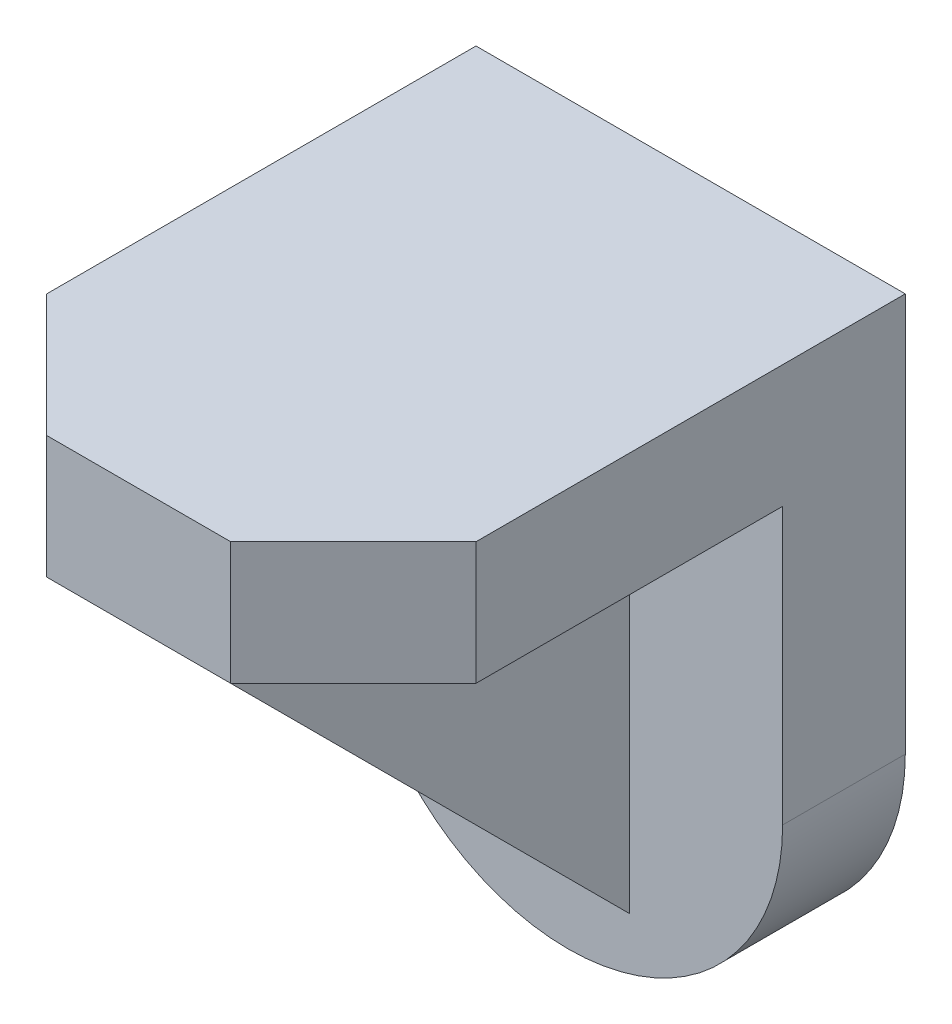
SolidWorks part; units mm, degrees
ref_plane "Front Plane" through (0, 0, 0) normal (0, 0, 1) x (1, 0, 0)
ref_plane "Top Plane" through (0, 0, 0) normal (0, 1, 0) x (1, 0, 0)
ref_plane "Right Plane" through (0, 0, 0) normal (1, 0, 0) x (0, 0, -1)
sketch "Sketch1" plane through (0, 0, 0) normal (0, 1, 0) x (1, 0, 0)
  line L0 (-68.9905, 0) -> (91.9874, 0) construction
  line L1 (0, 55.6183) -> (0, -65.6688) construction
  line L3 (-21, 27) -> (21, 27)
  line L4 (-21, 27) -> (-21, -27)
  line L5 (-21, -27) -> (21, -27)
  line L6 (21, 27) -> (21, -27)
  line L7 (-21, 27) -> (21, -27) construction
  line L8 (-21, -27) -> (21, 27) construction
  point P5 (0, 0)
  dimension "D1" = 54
  dimension "D2" = 42
extrude "Boss-Extrude1" add sketch "Sketch1" along normal blind 12
chamfer "Chamfer2" distance 12 2 edges at (21, 6, 27) (-21, 6, 27)
sketch "Sketch2" plane through (0, 0, -27) normal (0, 0, -1) x (-1, 0, 0)
  line L0 (21, 0) -> (21, -27)
  line L1 (-21, 0) -> (-21, -27)
  line L2 (-21, 0) -> (21, 0) construction
  line L7 (-21, 0) -> (21, 0)
  line L8 (21, 0) -> (21, 12)
  line L9 (21, 12) -> (-21, 12)
  line L10 (-21, 12) -> (-21, 0)
  line L11 (-21, 0) -> (21, 0)
  arc A0 (-21, -27) -> (21, -27) centre (0, -27) ccw
  dimension "D1" = 42
  dimension "D3" = 0
  dimension "D2" = 27
extrude "Boss-Extrude2" add sketch "Sketch2" against normal blind 12
sketch "Sketch8" plane through (0, 0, 0) normal (1, 0, 0) x (0, 0, -1)
  line L0 (15, -42) -> (15, 0)
  line L1 (15, -27) -> (15, -48) construction
  line L2 (15, -42) -> (-27, 0)
  line L3 (-27, 0) -> (15, 0)
  dimension "D1" = 42
extrude "Boss-Extrude3" add sketch "Sketch8" along normal mid plane 12
